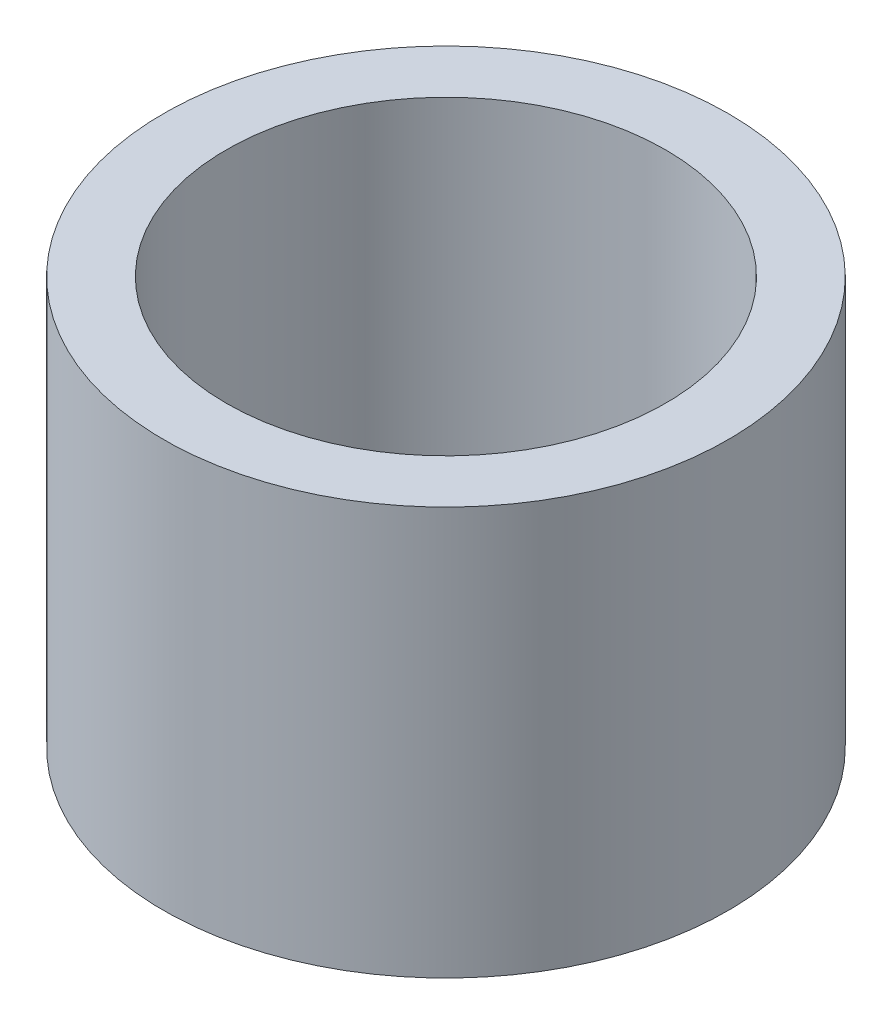
SolidWorks part; units mm, degrees
ref_plane "Alzado" through (0, 0, 0) normal (0, 0, 1) x (1, 0, 0)
ref_plane "Planta" through (0, 0, 0) normal (0, 1, 0) x (1, 0, 0)
ref_plane "Vista lateral" through (0, 0, 0) normal (1, 0, 0) x (0, 0, -1)
sketch "Croquis1" plane through (0, 0, 0) normal (0, 1, 0) x (1, 0, 0)
  circle A0 centre (0, 0) radius 7
  circle A1 centre (0, 0) radius 9
  dimension "D1" = 18
  dimension "D2" = 14
extrude "Saliente-Extruir1" add sketch "Croquis1" along normal blind 13
